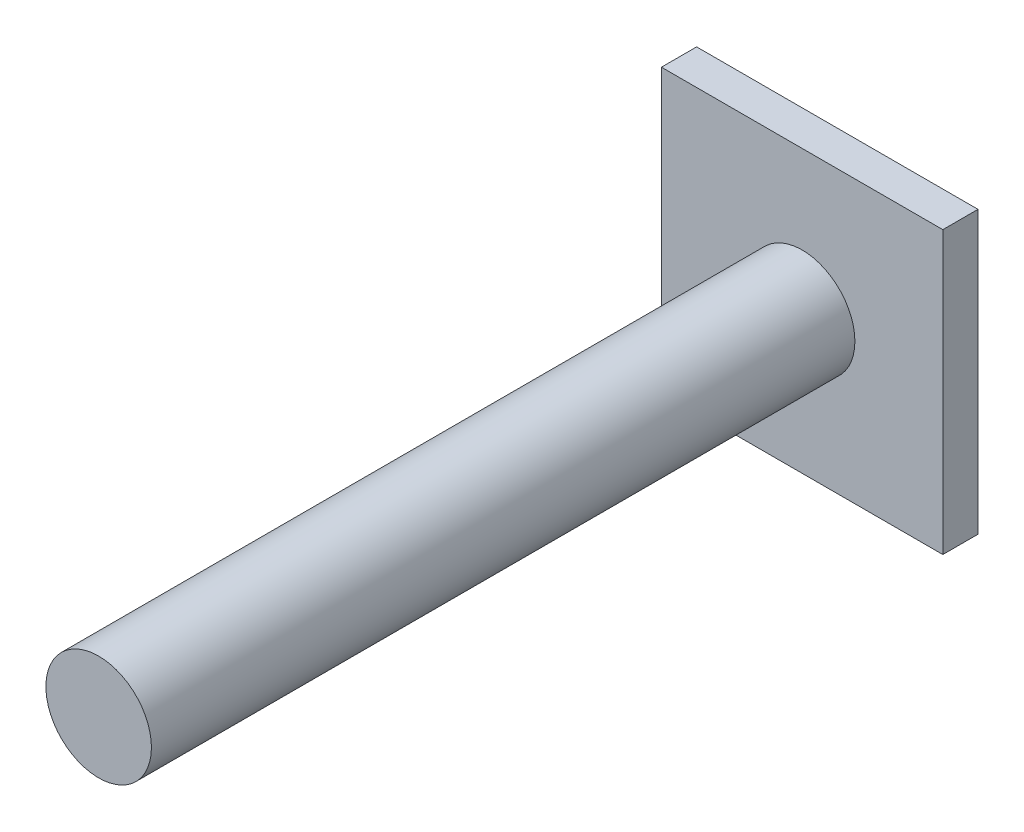
SolidWorks part; units mm, degrees
ref_plane "Plano frontal" through (0, 0, 0) normal (0, 0, 1) x (1, 0, 0)
ref_plane "Plano superior" through (0, 0, 0) normal (0, 1, 0) x (1, 0, 0)
ref_plane "Plano direito" through (0, 0, 0) normal (1, 0, 0) x (0, 0, -1)
sketch "Esboço1" plane through (0, 0, 0) normal (0, 0, 1) x (1, 0, 0)
  line L0 (0, 40) -> (40, 0) construction
  line L1 (0, 0) -> (40, 0)
  line L2 (0, 0) -> (0, 40)
  line L3 (0, 40) -> (40, 40)
  line L4 (40, 0) -> (40, 40)
  circle A0 centre (20, 20) radius 7 construction
  dimension "D2" = 14
  dimension "D1" = 40
extrude "Ressalto-extrusão1" add sketch "Esboço1" along normal blind 5
sketch "Esboço2" plane through (0, 0, 5) normal (0, 0, 1) x (1, 0, 0)
  line L0 (0, 40) -> (40, 0) construction
  circle A0 centre (20, 20) radius 7.5
  dimension "D1" = 15
extrude "Ressalto-extrusão2" add sketch "Esboço2" along normal blind 100
